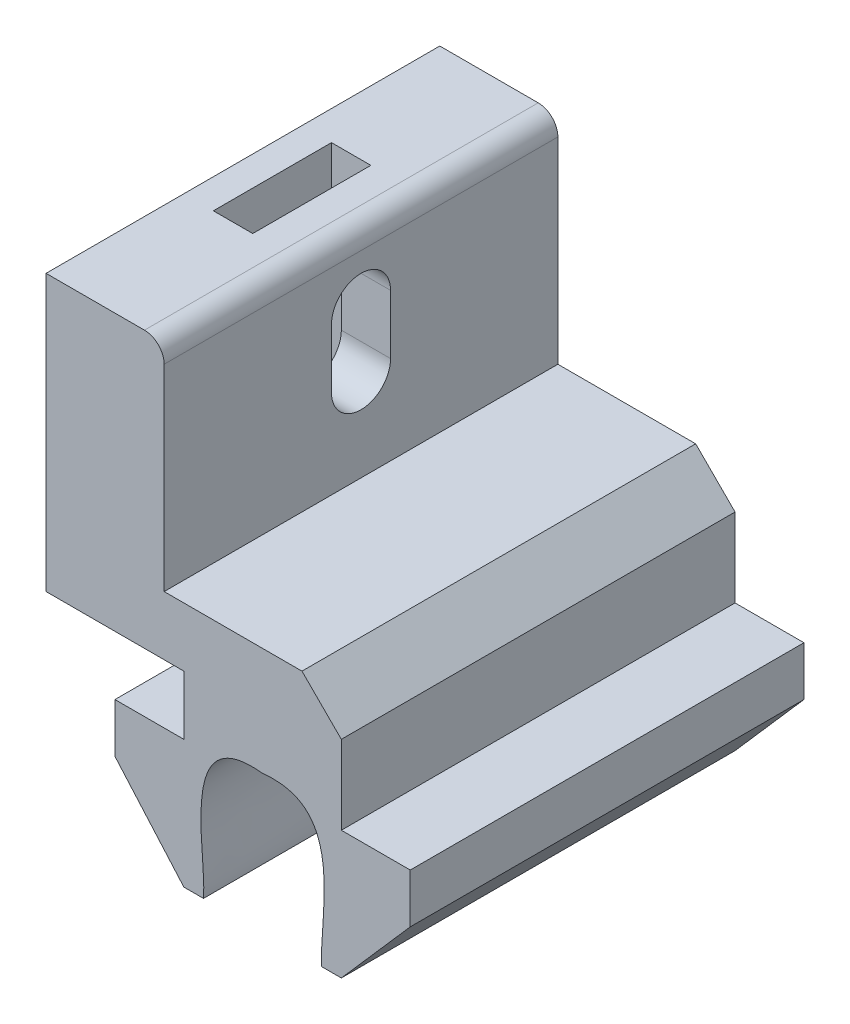
SolidWorks part; units mm, degrees
ref_plane "Piano frontale" through (0, 0, 0) normal (0, 0, 1) x (1, 0, 0)
ref_plane "Piano superiore" through (0, 0, 0) normal (0, 1, 0) x (1, 0, 0)
ref_plane "Piano destro" through (0, 0, 0) normal (1, 0, 0) x (0, 0, -1)
sketch "Schizzo2" plane through (0, 0, 0) normal (0, 0, 1) x (1, 0, 0)
  line L0 (0, 0) -> (0, 12.9875) construction
  line L1 (-4, 9.5) -> (-11, 9.5)
  line L2 (-11, 9.5) -> (-11, 23.5)
  line L3 (-11, 23.5) -> (-6, 23.5)
  line L4 (-5, 22.5) -> (-5, 12.5)
  line L5 (-5, 12.5) -> (4, 12.5)
  line L6 (4, 12.5) -> (4, 9.5)
  line L13 (-4, 0) -> (4, 0)
  line L14 (-7.5, 4) -> (-4, 0)
  line L15 (-7.5, 6.5) -> (-7.5, 4)
  line L16 (-4, 6.5) -> (-7.5, 6.5)
  line L17 (-4, 9.5) -> (-4, 6.5)
  line L44 (7.5, 4) -> (4, 0)
  line L45 (7.5, 6.5) -> (7.5, 4)
  line L46 (4, 6.5) -> (7.5, 6.5)
  line L72 (4, 9.5) -> (4, 6.5)
  arc A0 (-6, 23.5) -> (-5, 22.5) centre (-6, 22.5) cw
  point P9 (-5, 23.5)
  dimension "D11" = 1
  dimension "D1" = 8
  dimension "D2" = 4
  dimension "D3" = 2.5
  dimension "D4" = 8
  dimension "D5" = 3
  dimension "D6" = 15
  dimension "D7" = 11
  dimension "D8" = 6
  dimension "D9" = 3
  dimension "D10" = 14
extrude "Estrusione-Estrusione1" add sketch "Schizzo2" against normal blind 20
sketch "Schizzo6" plane through (-11, 0, 0) normal (-1, 0, 0) x (0, 0, 1)
  line L0 (0, 23.5) -> (0, 9.5) construction
  line L1 (-20, 23.5) -> (0, 23.5) construction
  line L2 (-10, 20) -> (-10, 17) construction
  line L3 (-8.5, 20) -> (-8.5, 17)
  line L4 (-11.5, 20) -> (-11.5, 17)
  line L5 (-20, 9.5) -> (0, 9.5) construction
  arc A1 (-8.5, 20) -> (-11.5, 20) centre (-10, 20) ccw
  arc A2 (-11.5, 17) -> (-8.5, 17) centre (-10, 17) ccw
  point P6 (-10, 18.5)
  dimension "D2" = 1.5
  dimension "D1" = 10
  dimension "D3" = 3.5
  dimension "D4" = 3
  dimension "D5" = 9
extrude "Taglio-Estrusione1" cut sketch "Schizzo6" against normal up to next
sketch "Schizzo11" plane through (0, 0, -20) normal (0, 0, -1) x (-1, 0, 0)
  line L0 (4, 0) -> (-4, 0) construction
  line L1 (7.5, 6.5) -> (7.5, 4) construction
  text T0 "3" font "Century Gothic" height 6.5
  dimension "D1" = 1
  dimension "D2" = 10.5
extrude "Estrusione-Estrusione4" [suppressed] add sketch "Schizzo11" along normal blind 0.6
sketch "Schizzo12" plane through (0, 23.5, 0) normal (0, 1, 0) x (1, 0, 0)
  line L0 (-6, 10) -> (-11, 10) construction
  line L1 (-6, 20) -> (-6, 0) construction
  line L2 (-11, 20) -> (-11, 0) construction
  line L4 (-7.5, 7) -> (-9.5, 7)
  line L5 (-7.5, 7) -> (-7.5, 13)
  line L6 (-7.5, 13) -> (-9.5, 13)
  line L7 (-9.5, 7) -> (-9.5, 13)
  line L8 (-7.5, 7) -> (-9.5, 13) construction
  line L9 (-7.5, 13) -> (-9.5, 7) construction
  point P6 (-8.5, 10)
  dimension "D1" = 2
  dimension "D2" = 6
extrude "Taglio-Estrusione2" cut sketch "Schizzo12" against normal blind 11
sketch "Schizzo13" plane through (0, 0, -20) normal (0, 0, -1) x (-1, 0, 0)
  line L0 (4, 0) -> (-4, 0) construction
  line L1 (0, 7) -> (0, 4.3043) construction
  spline S0 degree 3 poles (-3, 0) (-2.8317, 2.145) (-4.3776, 7.5007) (0, 7) knots 0 0 0 0 1 1 1 1
  spline S1 degree 3 poles (3, 0) (2.8317, 2.145) (4.3776, 7.5007) (0, 7) knots 0 0 0 0 1 1 1 1
  dimension "D1" = 7
  dimension "D2" = 3
extrude "Taglio-Estrusione3" cut sketch "Schizzo13" against normal through all and the other way through all
chamfer "Smusso1" distance 2 angle 45 1 edges at (4, 12.5, -10)
